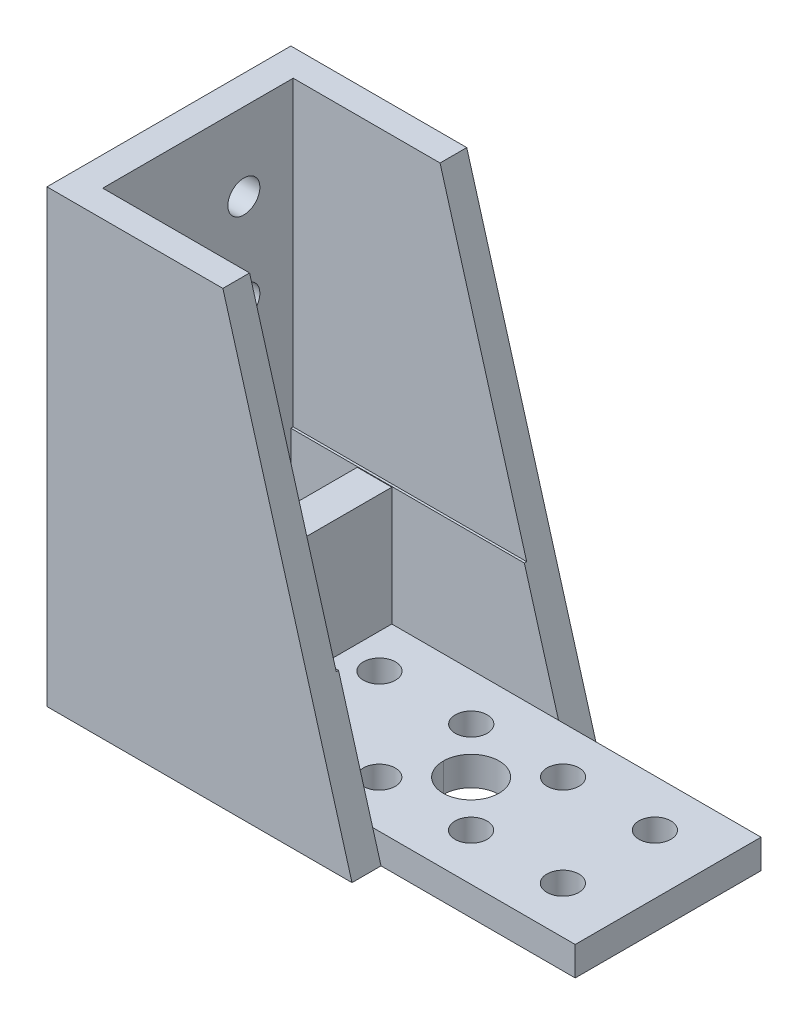
SolidWorks part; units mm, degrees
ref_plane "Front Plane" through (0, 0, 0) normal (0, 0, 1) x (1, 0, 0)
ref_plane "Top Plane" through (0, 0, 0) normal (0, 1, 0) x (1, 0, 0)
ref_plane "Right Plane" through (0, 0, 0) normal (1, 0, 0) x (0, 0, -1)
sketch "Sketch1" plane through (0, 0, 0) normal (0, 0, 1) x (1, 0, 0)
  line L0 (-22.5416, 5.3233) -> (-8.4223, -43.8956)
  line L2 (-38.6011, 5.3233) -> (-38.6011, -43.8956)
  line L3 (-38.6011, -43.8956) -> (-8.4223, -43.8956)
  line L4 (-38.0931, -43.3956) -> (-38.0931, 9.6984) construction
  line L5 (-22.5416, 5.3233) -> (-38.6011, 5.3233)
  line L6 (-35.3071, -43.8956) -> (17.7869, -43.8956) construction
  dimension "D1" = 0.508
extrude "Boss-Extrude1" add sketch "Sketch1" along normal blind 3.175
sketch "Sketch2" plane through (-38.6011, 0, 0) normal (-1, 0, 0) x (0, 0, 1)
  line L1 (3.175, 5.3233) -> (-10.16, 5.3233)
  line L2 (3.175, 5.3233) -> (3.175, -43.8956)
  line L3 (3.175, -43.8956) -> (-10.16, -43.8956)
  line L4 (-10.16, 5.3233) -> (-10.16, -43.8956)
  circle A0 centre (-5.1395, -3.1796) radius 1.75
  circle A1 centre (-5.1395, -13.2205) radius 1.75
  circle A2 centre (-5.1395, -13.2205) radius 1.75 construction
extrude "Boss-Extrude2" add sketch "Sketch2" along normal blind 3.175
sketch "Sketch3" plane through (0, 0, 0) normal (0, 0, -1) x (-1, 0, 0)
  line L0 (-17.7869, -43.8956) -> (35.3071, -43.8956) construction
  line L1 (-12.8105, -43.8956) -> (33.5365, -43.8956)
  line L2 (-12.8105, -43.8956) -> (-12.8105, -40.7206)
  line L3 (-12.8105, -40.7206) -> (33.5365, -40.7206)
  line L4 (33.5365, -43.8956) -> (33.5365, -40.7206)
  dimension "D1" = 3.175
extrude "Boss-Extrude3" add sketch "Sketch3" along normal up to surface (10.16 mm away) up to face at (-40.1886, -19.2862, -10.16)
sketch "Sketch4" plane through (0, -40.7206, 0) normal (0, 1, 0) x (1, 0, 0)
  circle A1 centre (-3.7067, 5.1295) radius 1.75
  circle A2 centre (-3.7067, 5.1295) radius 1.75
  circle A3 centre (-23.7885, 5.1295) radius 1.75
  circle A4 centre (-23.7885, 5.1295) radius 1.75
  circle A5 centre (6.3342, 15.1705) radius 1.75
  circle A6 centre (6.3342, 15.1705) radius 1.75
  circle A7 centre (-8.7271, 10.15) radius 3.05
  circle A8 centre (-8.7271, 10.15) radius 3.05
  circle A9 centre (6.3342, 5.1295) radius 1.75
  circle A10 centre (6.3342, 5.1295) radius 1.75
  circle A11 centre (-13.7476, 5.1295) radius 1.75
  circle A12 centre (-13.7476, 5.1295) radius 1.75
  circle A13 centre (-23.7885, 15.1705) radius 1.75
  circle A14 centre (-23.7885, 15.1705) radius 1.75
  circle A15 centre (-3.7067, 15.1705) radius 1.75
  circle A16 centre (-3.7067, 15.1705) radius 1.75
  circle A17 centre (-13.7476, 15.1705) radius 1.75
  circle A18 centre (-13.7476, 15.1705) radius 1.75
  dimension "D1" = 0
  dimension "D2" = 0
  dimension "D3" = 0
  dimension "D4" = 0
  dimension "D5" = 0
  dimension "D6" = 0
  dimension "D7" = 0
  dimension "D8" = 0
  dimension "D9" = 0
extrude "Cut-Extrude1" cut sketch "Sketch4" against normal blind 8.255
mirror "Mirror3" about plane through (-41.7761, 5.3233, -10.16) normal (0, 0, 1) of bodies 104
sketch "Sketch5" plane through (0, -40.7206, 0) normal (0, 1, 0) x (1, 0, 0)
  line L0 (-22.5416, 20.32) -> (-38.6011, 20.32) construction
  line L1 (-31.3387, 20.32) -> (-27.5655, 20.32)
  line L2 (-31.3387, 20.32) -> (-31.3387, 0)
  line L3 (-31.3387, 0) -> (-27.5655, 0)
  line L4 (-27.5655, 20.32) -> (-27.5655, 0)
  line L5 (-33.5365, 0) -> (-9.3331, 0) construction
extrude "Boss-Extrude4" add sketch "Sketch5" along normal blind 12.954
sketch "Sketch6" plane through (0, 5.3233, 0) normal (0, 1, 0) x (1, 0, 0)
  line L1 (-38.6011, 20.32) -> (-3.9017, 20.32)
  line L2 (-38.6011, 20.32) -> (-38.6011, 20.574)
  line L3 (-38.6011, 20.574) -> (-3.9017, 20.574)
  line L4 (-3.9017, 20.32) -> (-3.9017, 20.574)
  line L5 (-38.6011, 0) -> (-3.9017, 0)
  line L6 (-38.6011, 0) -> (-38.6011, -0.254)
  line L7 (-38.6011, -0.254) -> (-3.9017, -0.254)
  line L8 (-3.9017, 0) -> (-3.9017, -0.254)
  dimension "D1" = 0.254
  dimension "D2" = 0.254
extrude "Cut-Extrude2" cut sketch "Sketch6" against normal blind 33.02
